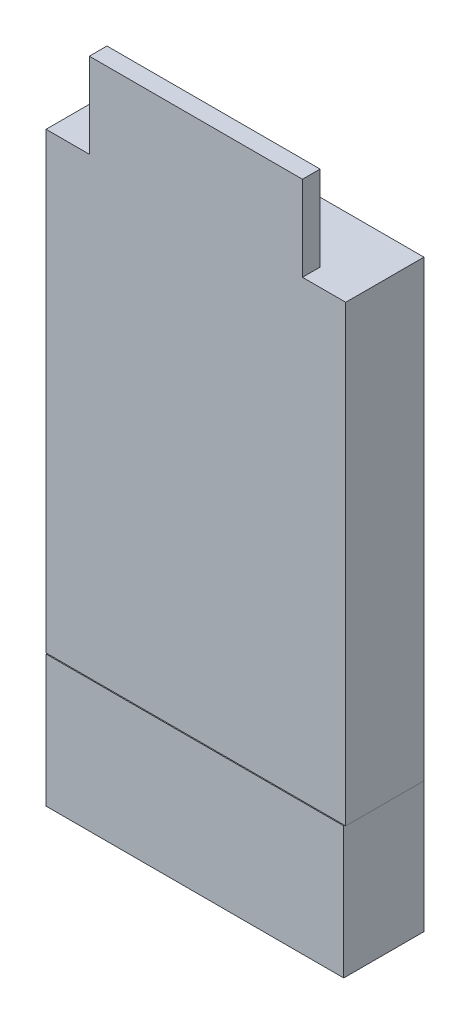
SolidWorks part; units mm, degrees
ref_plane "Přední rovina" through (0, 0, 0) normal (0, 0, 1) x (1, 0, 0)
ref_plane "Horní rovina" through (0, 0, 0) normal (0, 1, 0) x (1, 0, 0)
ref_plane "Pravá rovina" through (0, 0, 0) normal (1, 0, 0) x (0, 0, -1)
sketch "Skica1" plane through (0, 0, 0) normal (0, 0, 1) x (1, 0, 0)
  line L1 (-9.285, -4.11) -> (9.285, -4.11)
  line L2 (-9.285, -4.11) -> (-9.285, 4.11)
  line L3 (-9.285, 4.11) -> (9.285, 4.11)
  line L4 (9.285, -4.11) -> (9.285, 4.11)
  line L5 (-9.285, -4.11) -> (9.285, 4.11) construction
  line L6 (-9.285, 4.11) -> (9.285, -4.11) construction
  point P0 (0, 0)
  dimension "D1" = 18.57
  dimension "D2" = 8.22
extrude "Přidat vysunutím1" add sketch "Skica1" along normal blind 5
sketch "Skica2" plane through (0, 4.11, 0) normal (0, 1, 0) x (1, 0, 0)
  line L0 (0, -5) -> (0, 0) construction
  line L1 (9.35, -0.06) -> (-9.35, -0.06)
  line L2 (9.35, -0.06) -> (9.35, -4.94)
  line L3 (9.35, -4.94) -> (-9.35, -4.94)
  line L4 (-9.35, -0.06) -> (-9.35, -4.94)
  line L5 (9.35, -0.06) -> (-9.35, -4.94) construction
  line L6 (9.35, -4.94) -> (-9.35, -0.06) construction
  line L7 (9.285, -5) -> (-9.285, -5) construction
  line L8 (9.285, 0) -> (-9.285, 0) construction
  line L9 (-9.285, -2.5) -> (9.35, -2.5) construction
  line L10 (-9.285, -5) -> (-9.285, 0) construction
  line L11 (9.35, -2.5) -> (-9.35, -2.5) construction
  point P0 (0, -2.5)
  dimension "D1" = 18.7
  dimension "D2" = 4.88
extrude "Přidat vysunutím2" add sketch "Skica2" along normal blind 28.3
sketch "Skica3" plane through (0, 32.41, 0) normal (0, 1, 0) x (1, 0, 0)
  line L0 (-9.35, -4.94) -> (9.35, -4.94) construction
  line L1 (6.65, -4.94) -> (-6.65, -4.94)
  line L2 (6.65, -4.94) -> (6.65, -3.84)
  line L3 (6.65, -3.84) -> (-6.65, -3.84)
  line L4 (-6.65, -4.94) -> (-6.65, -3.84)
  line L5 (-9.35, -0.06) -> (-9.35, -4.94) construction
  line L6 (9.35, -4.94) -> (9.35, -0.06) construction
  dimension "D1" = 2.7
  dimension "D2" = 2.7
  dimension "D3" = 1.1
extrude "Přidat vysunutím3" add sketch "Skica3" along normal blind 5.3
